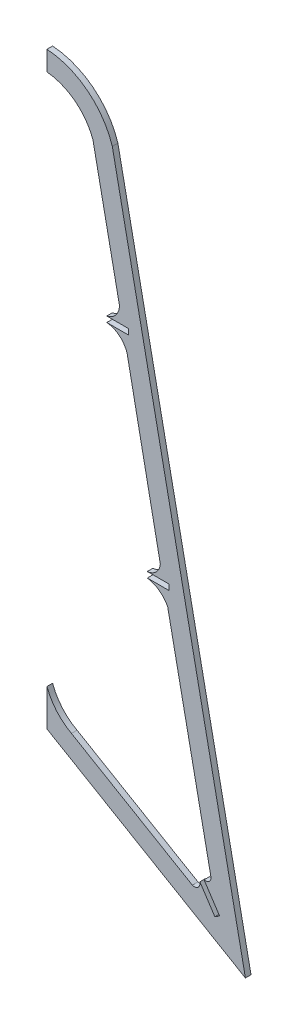
SolidWorks part; units mm, degrees
ref_plane "前视基准面" through (0, 0, 0) normal (0, 0, 1) x (1, 0, 0)
ref_plane "上视基准面" through (0, 0, 0) normal (0, 1, 0) x (1, 0, 0)
ref_plane "右视基准面" through (0, 0, 0) normal (1, 0, 0) x (0, 0, -1)
sketch "Model" plane through (0, 0, 0) normal (0, 0, 1) x (1, 0, 0)
  line L0 (-97.0117, 42.4649) -> (-144.4635, 275.4766)
  line L1 (-167.7436, 83.9602) -> (-97.0117, 42.4649)
  line L2 (-159.0236, 86.9602) -> (-115.911, 61.6679)
  line L3 (-151.3547, 274.0119) -> (-141.8972, 227.5712)
  line L4 (-139.1701, 214.1798) -> (-127.3476, 155.1111)
  line L5 (-124.7181, 143.2131) -> (-109.3141, 67.5722)
  line L6 (-107.8883, 55.921) -> (-106.2214, 57.0262)
  line L7 (-146.4326, 222.1124) -> (-138.68, 222.1124)
  line L8 (-138.68, 222.1124) -> (-138.68, 220.1124)
  line L9 (-138.68, 220.1124) -> (-146.4326, 220.1124)
  line L10 (-131.9751, 148.4656) -> (-124.2025, 148.4656)
  line L11 (-124.2025, 148.4656) -> (-124.2025, 150.4656)
  line L12 (-124.2025, 150.4656) -> (-131.9917, 150.4665)
  line L13 (-113.2505, 64.0491) -> (-107.8883, 55.921)
  line L14 (-106.2214, 57.0262) -> (-111.744, 65.3974)
  line L15 (-167.7436, 97.107) -> (-167.7436, 83.9602)
  line L16 (-167.7436, 293.8107) -> (-167.7458, 286.7876)
  arc A0 (-144.4635, 275.4766) -> (-167.7436, 293.8107) centre (-169.5814, 267.5299) ccw
  arc A1 (-151.3547, 274.0119) -> (-167.7458, 286.7876) centre (-169.5814, 267.5299) ccw
  arc A2 (-146.4326, 222.1124) -> (-141.8972, 227.5712) centre (-147.6046, 227.6996) ccw
  arc A3 (-139.1701, 214.1798) -> (-146.4326, 220.1124) centre (-147.2084, 211.7512) ccw
  arc A4 (-131.9917, 150.4665) -> (-127.3476, 155.1111) centre (-132.4049, 155.5238) ccw
  arc A5 (-124.7181, 143.2131) -> (-131.9751, 148.4656) centre (-133.4455, 138.7945) ccw
  arc A6 (-115.911, 61.6679) -> (-113.2505, 64.0491) centre (-115.2224, 63.5754) ccw
  arc A7 (-111.744, 65.3974) -> (-109.3141, 67.5722) centre (-111.2495, 67.2898) ccw
  arc A8 (-167.7436, 97.107) -> (-159.0236, 86.9602) centre (-150.1168, 103.4348) ccw
  point P35 (-107.8035, 55.8546)
  point P36 (-107.8883, 55.9004)
extrude "凸台-拉伸1" add sketch "Model" along normal blind 2
